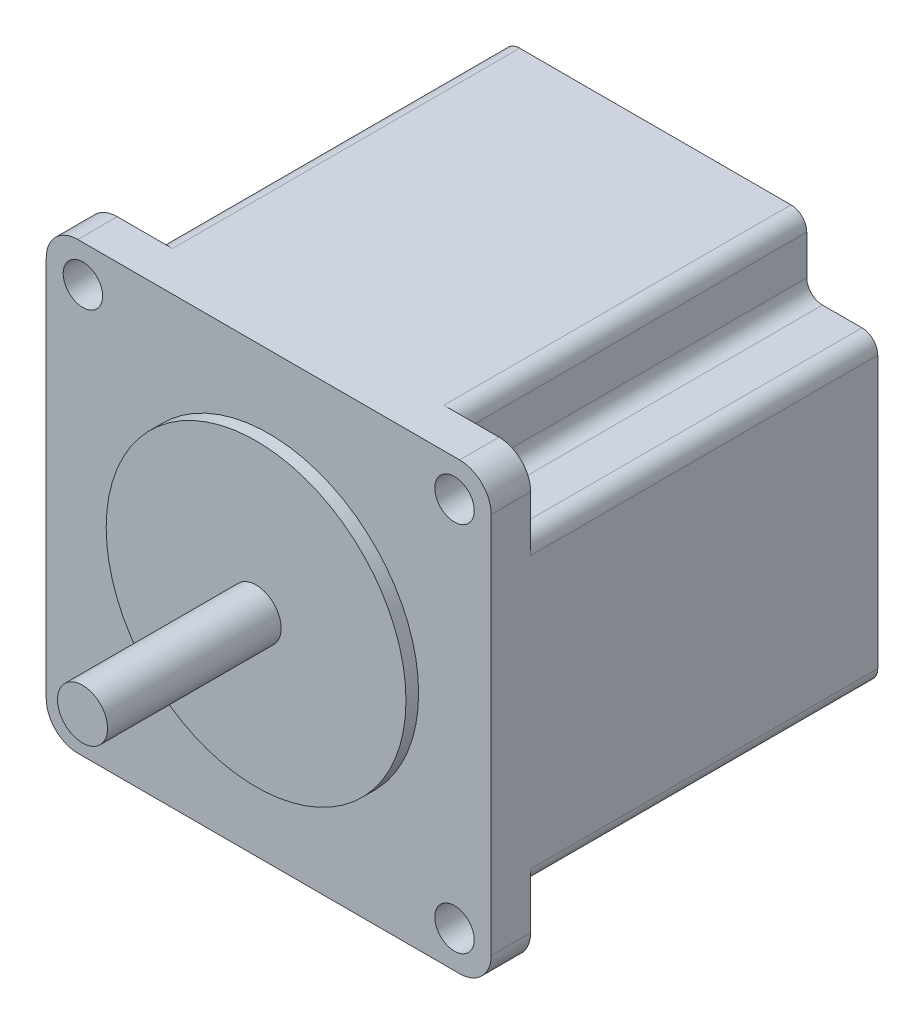
SolidWorks part; units mm, degrees
ref_plane "Alzado" through (0, 0, 0) normal (0, 0, 1) x (1, 0, 0)
ref_plane "Planta" through (0, 0, 0) normal (0, 1, 0) x (1, 0, 0)
ref_plane "Vista lateral" through (0, 0, 0) normal (1, 0, 0) x (0, 0, -1)
sketch "Croquis1" plane through (0, 0, 0) normal (0, 0, 1) x (1, 0, 0)
  line L1 (-28.2, 28.2) -> (28.2, 28.2)
  line L2 (-28.2, 28.2) -> (-28.2, -28.2)
  line L3 (-28.2, -28.2) -> (28.2, -28.2)
  line L4 (28.2, 28.2) -> (28.2, -28.2)
  line L5 (-28.2, 28.2) -> (28.2, -28.2) construction
  line L6 (-28.2, -28.2) -> (28.2, 28.2) construction
  point P0 (0, 0)
  dimension "D1" = 56.4
  dimension "D2" = 56.4
extrude "Saliente-Extruir1" add sketch "Croquis1" along normal blind 49
sketch "Croquis2" plane through (0, 0, 49) normal (0, 0, 1) x (1, 0, 0)
  circle A0 centre (0, 0) radius 19
  dimension "D1" = 38
extrude "Saliente-Extruir2" add sketch "Croquis2" along normal blind 1.6
sketch "Croquis3" plane through (0, 0, 50.6) normal (0, 0, 1) x (1, 0, 0)
  circle A0 centre (0, 0) radius 3.175
  dimension "D1" = 6.35
extrude "Saliente-Extruir3" add sketch "Croquis3" along normal blind 22
sketch "Croquis4" plane through (0, 0, 49) normal (0, 0, 1) x (1, 0, 0)
  line L1 (-23.55, 23.55) -> (23.55, 23.55) construction
  line L2 (-23.55, 23.55) -> (-23.55, -23.55) construction
  line L3 (-23.55, -23.55) -> (23.55, -23.55) construction
  line L4 (23.55, 23.55) -> (23.55, -23.55) construction
  line L5 (-23.55, 23.55) -> (23.55, -23.55) construction
  line L6 (-23.55, -23.55) -> (23.55, 23.55) construction
  circle A0 centre (23.55, 23.55) radius 2.5
  circle A1 centre (-23.55, 23.55) radius 2.5
  circle A2 centre (-23.55, -23.55) radius 2.5
  circle A3 centre (23.55, -23.55) radius 2.5
  point P0 (0, 0)
  dimension "D3" = 5
  dimension "D4" = 5
  dimension "D5" = 5
  dimension "D6" = 5
  dimension "D1" = 47.1
  dimension "D2" = 47.1
extrude "Cortar-Extruir1" cut sketch "Croquis4" against normal through all
sketch "Croquis5" plane through (0, 0, 0) normal (0, 0, -1) x (-1, 0, 0)
  line L1 (-28.2, 28.2) -> (-19.2, 28.2)
  line L2 (-28.2, 28.2) -> (-28.2, 19.2)
  line L3 (-28.2, 19.2) -> (-19.2, 19.2)
  line L4 (-19.2, 28.2) -> (-19.2, 19.2)
  line L5 (28.2, 28.2) -> (19.2, 28.2)
  line L6 (28.2, 28.2) -> (28.2, 19.2)
  line L7 (28.2, 19.2) -> (19.2, 19.2)
  line L8 (19.2, 28.2) -> (19.2, 19.2)
  line L9 (28.2, -28.2) -> (19.2, -28.2)
  line L10 (28.2, -28.2) -> (28.2, -19.2)
  line L11 (28.2, -19.2) -> (19.2, -19.2)
  line L12 (19.2, -28.2) -> (19.2, -19.2)
  line L13 (-28.2, -28.2) -> (-19.2, -28.2)
  line L14 (-28.2, -28.2) -> (-28.2, -19.2)
  line L15 (-28.2, -19.2) -> (-19.2, -19.2)
  line L16 (-19.2, -28.2) -> (-19.2, -19.2)
  dimension "D1" = 9
  dimension "D2" = 9
  dimension "D3" = 9
  dimension "D4" = 9
  dimension "D5" = 9
  dimension "D6" = 9
  dimension "D7" = 9
  dimension "D8" = 9
extrude "Cortar-Extruir2" cut sketch "Croquis5" against normal blind 44
fillet "Redondeo1" radius 4 4 edges at (28.2, -28.2, 46.5) (28.2, 28.2, 46.5) (-28.2, -28.2, 46.5) (-28.2, 28.2, 46.5)
fillet "Redondeo2" radius 2 12 edges at (-19.2, 28.2, 22) (-19.2, 19.2, 22) (-28.2, 19.2, 22) (-28.2, -19.2, 22) (-19.2, -19.2, 22) (-19.2, -28.2, 22) (19.2, -28.2, 22) (19.2, -19.2, 22) (28.2, -19.2, 22) (28.2, 19.2, 22) (19.2, 19.2, 22) (19.2, 28.2, 22)
